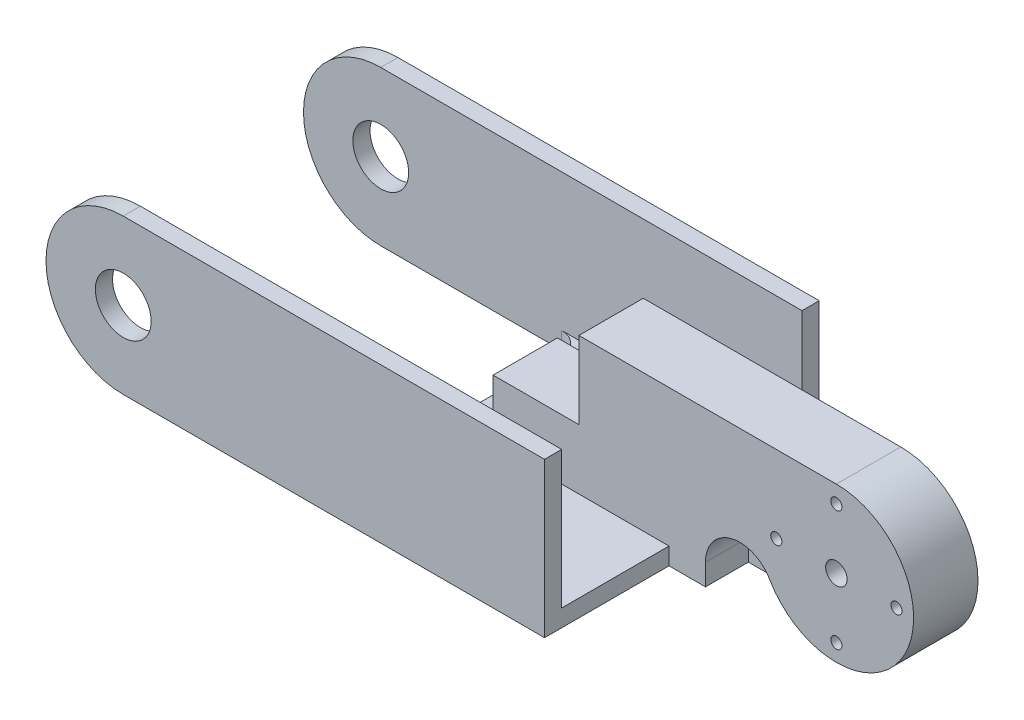
SolidWorks part; units mm, degrees
ref_plane "Front Plane" through (0, 0, 0) normal (0, 0, 1) x (1, 0, 0)
ref_plane "Top Plane" through (0, 0, 0) normal (0, 1, 0) x (1, 0, 0)
ref_plane "Right Plane" through (0, 0, 0) normal (1, 0, 0) x (0, 0, -1)
sketch "Sketch1" plane through (0, 0, 0) normal (0, 0, 1) x (1, 0, 0)
  line L1 (0, 0) -> (-98.17, 0)
  line L2 (0, 0) -> (0, 36)
  line L3 (0, 36) -> (-98.17, 36)
  arc A0 (-98.17, 36) -> (-98.17, 0) centre (-98.17, 18) ccw
  point P4 (-58.585, 18)
  dimension "D1" = 18
  dimension "D2" = 98.17
extrude "Boss-Extrude1" add sketch "Sketch1" along normal blind 4
sketch "Sketch2" plane through (0, 0, 4) normal (0, 0, 1) x (1, 0, 0)
  line L1 (0, 0) -> (-51, 0)
  line L2 (0, 0) -> (0, 4)
  line L3 (0, 4) -> (-51, 4)
  line L4 (-51, 0) -> (-51, 4)
  line L5 (0, 0) -> (-51, 4) construction
  line L6 (0, 4) -> (-51, 0) construction
  point P4 (-24.1918, 2.1558)
extrude "Boss-Extrude2" add sketch "Sketch2" along normal blind 16
sketch "Sketch3" plane through (0, 0, 20) normal (0, 0, 1) x (1, 0, 0)
  line L0 (39, 18) -> (38.9995, 17.9997)
  line L2 (-51, 0) -> (-51, 4)
  line L6 (-51, 0) -> (39, 0)
  line L9 (-21, 18) -> (-41, 18)
  line L10 (-41, 4) -> (-41, 18)
  line L11 (-21, 36) -> (39, 36)
  line L16 (-21, 18) -> (-21, 36)
  line L18 (-51, 4) -> (-41, 4)
  arc A3 (39, 0) -> (39, 36) centre (39, 18) ccw
  point P4 (-25.5, 2)
  point P8 (-21.8464, 8.3476)
  point P15 (-17.4676, 27)
  point P19 (7.8028, 17.8669)
extrude "Boss-Extrude3" add sketch "Sketch3" along normal blind 15
sketch "Sketch4" plane through (0, 0, 35) normal (0, 0, 1) x (1, 0, 0)
  line L1 (0, 0) -> (-51, 0)
  line L2 (0, 0) -> (0, 4)
  line L3 (0, 4) -> (-51, 4)
  line L4 (-51, 0) -> (-51, 4)
  line L5 (0, 0) -> (-51, 4) construction
  line L6 (0, 4) -> (-51, 0) construction
  point P4 (-25.5, 2)
extrude "Boss-Extrude4" add sketch "Sketch4" along normal blind 25
sketch "Sketch5" plane through (0, 0, 60) normal (0, 0, 1) x (1, 0, 0)
  line L1 (0, 0) -> (-98.17, 0)
  line L2 (0, 0) -> (0, 36)
  line L3 (0, 36) -> (-98.17, 36)
  arc A0 (-98.17, 36) -> (-98.17, 0) centre (-98.17, 18) ccw
  point P4 (-58.585, 18)
  dimension "D1" = 98.17
extrude "Boss-Extrude5" add sketch "Sketch5" along normal blind 4
sketch "Sketch6" plane through (0, 0, 64) normal (0, 0, 1) x (1, 0, 0)
  circle A0 centre (-98.17, 18) radius 6.5
extrude "Cut-Extrude1" cut sketch "Sketch6" against normal through all
sketch "Sketch7" plane through (0, 0, 35) normal (0, 0, 1) x (1, 0, 0)
  circle A0 centre (39, 18) radius 2.5
extrude "Cut-Extrude2" cut sketch "Sketch7" against normal through all
sketch "Sketch8" plane through (0, 0, 35) normal (0, 0, 1) x (1, 0, 0)
  line L15 (8.4987, 4.9734) -> (8.4987, 0)
  line L18 (8.4987, 0) -> (39, 0)
  arc A5 (23.4488, 8.9724) -> (39, 0) centre (39.0213, 18) ccw
  arc A6 (23.4488, 8.9724) -> (8.4987, 4.9734) centre (16.4987, 5.0106) ccw
  dimension "D1" = 8
  dimension "D2" = 18
extrude "Cut-Extrude7" cut sketch "Sketch8" against normal blind 10
sketch "Sketch10" plane through (0, 0, 35) normal (0, 0, 1) x (1, 0, 0)
  point P0 (39, 32)
  point P2 (25, 18)
  point P4 (39, 4)
  point P6 (53, 18)
hole_wizard "M3x0.5 Tapped Hole1" positions "Sketch10" profile "Sketch11" tap size "M3x0.5" standard "JIS"
sketch "Sketch11" plane through (39, 32, 35) normal (1, 0, 0) x (0, -1, 0)
  line L0 (0, 0) -> (0, 9.7811)
  line L1 (0, 9.7811) -> (1.3, 9)
  line L2 (1.3, 9) -> (1.3, 0)
  line L5 (1.3, 0) -> (0, 0)
  line L10 (0, 9.7811) -> (-1.3, 9) construction
  line L11 (0, -6.35) -> (0, 107.95) construction
  dimension "Tap Drill Dia." = 2.6
  dimension "Tap Drill Depth" = 9
  dimension "Drill Angle" = 118
cosmetic thread "Hole Thread1" parameters "D1"=6, "D2"=3
cosmetic thread "Hole Thread2" parameters "D1"=6, "D2"=3
cosmetic thread "Hole Thread3" parameters "D1"=6, "D2"=3
cosmetic thread "Hole Thread4" parameters "D1"=6, "D2"=3
fillet "Fillet1" radius 5 2 edges at (-51, 2, 60) (-51, 2, 4)
